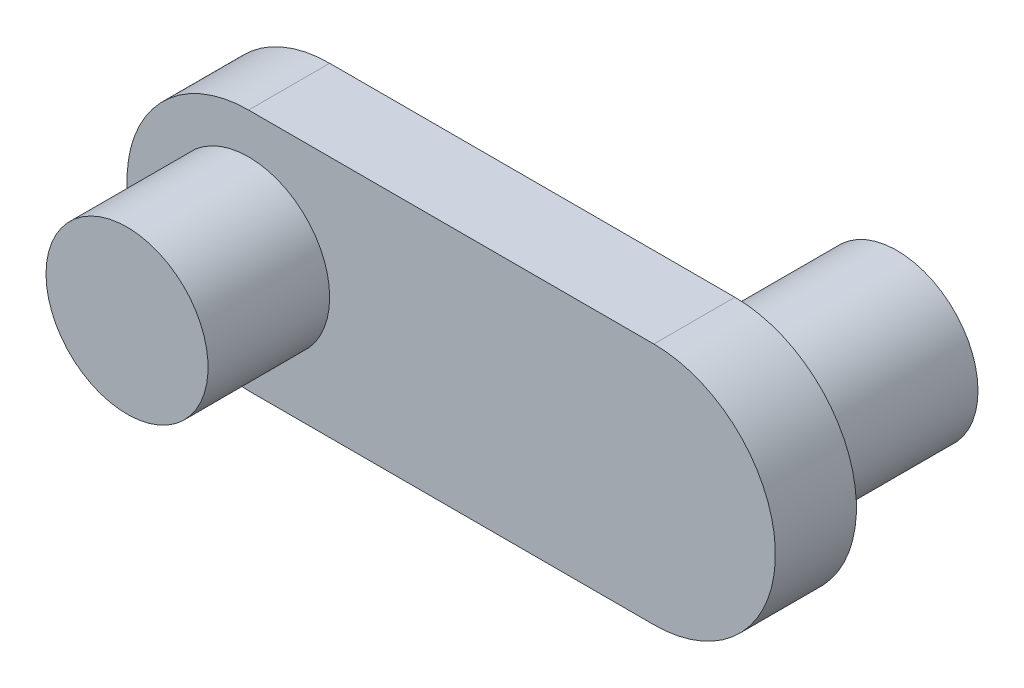
SolidWorks part; units mm, degrees
ref_plane "Front Plane" through (0, 0, 0) normal (0, 0, 1) x (1, 0, 0)
ref_plane "Top Plane" through (0, 0, 0) normal (0, 1, 0) x (1, 0, 0)
ref_plane "Right Plane" through (0, 0, 0) normal (1, 0, 0) x (0, 0, -1)
sketch "Sketch1" plane through (0, 0, 0) normal (0, 0, 1) x (1, 0, 0)
  line L0 (-95.0111, 0) -> (-45.0111, 0) construction
  line L3 (-95.0111, 15) -> (-45.0111, 15)
  line L4 (-95.0111, -15) -> (-45.0111, -15)
  arc A2 (-95.0111, 15) -> (-95.0111, -15) centre (-95.0111, 0) ccw
  arc A3 (-45.0111, -15) -> (-45.0111, 15) centre (-45.0111, 0) ccw
  circle A4 centre (-95.0111, 0) radius 10
  circle A5 centre (-45.0111, 0) radius 10
  point P3 (-70.0111, 0)
  dimension "D3" = 20
  dimension "D4" = 20
  dimension "D1" = 30
  dimension "D2" = 50
extrude "Boss-Extrude1" add sketch "Sketch1" along normal blind 10
sketch "Sketch2" plane through (0, 0, 10) normal (0, 0, 1) x (1, 0, 0)
  circle A0 centre (-45.0111, 0) radius 10
extrude "Boss-Extrude2" add sketch "Sketch2" against normal blind 30
sketch "Sketch3" plane through (0, 0, 0) normal (0, 0, -1) x (-1, 0, 0)
  circle A0 centre (95.0111, 0) radius 10
extrude "Boss-Extrude3" add sketch "Sketch3" against normal blind 25
